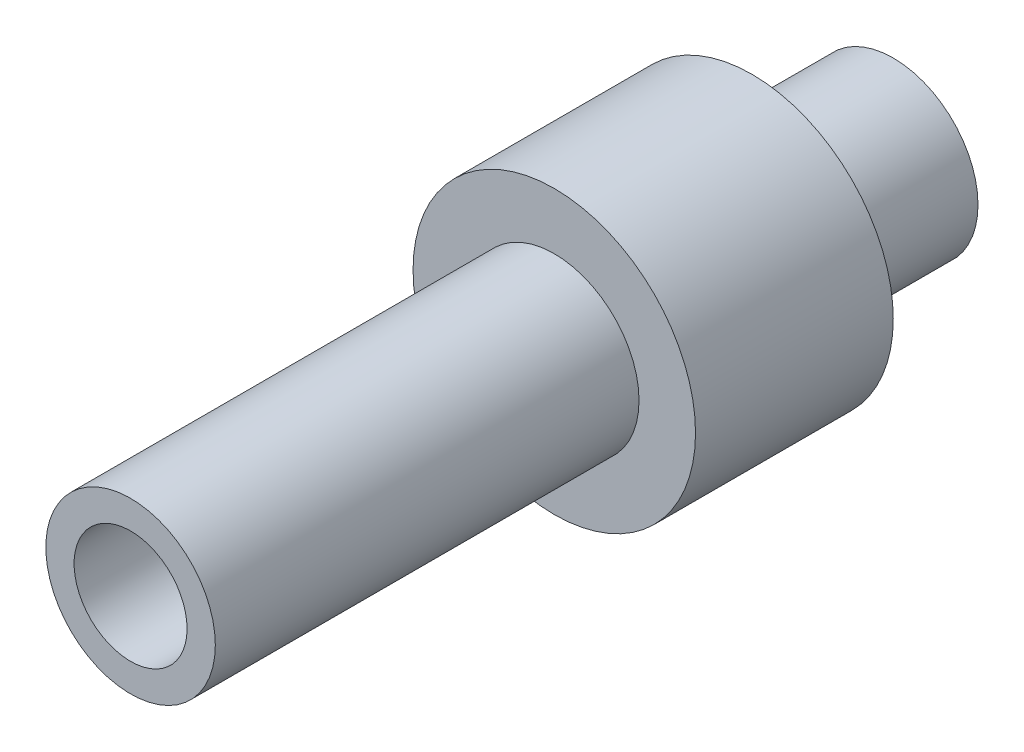
SolidWorks part; units mm, degrees
ref_plane "정면" through (0, 0, 0) normal (0, 0, 1) x (1, 0, 0)
ref_plane "윗면" through (0, 0, 0) normal (0, 1, 0) x (1, 0, 0)
ref_plane "우측면" through (0, 0, 0) normal (1, 0, 0) x (0, 0, -1)
sketch "스케치1" plane through (0, 0, 0) normal (0, 0, 1) x (1, 0, 0)
  circle A0 centre (0, 0) radius 5
extrude "돌출1" add sketch "스케치1" along normal blind 7
sketch "스케치2" plane through (0, 0, 7) normal (0, 0, 1) x (1, 0, 0)
  circle A0 centre (0, 0) radius 3
extrude "돌출2" add sketch "스케치2" along normal blind 15
sketch "스케치3" plane through (0, 0, 0) normal (0, 0, -1) x (-1, 0, 0)
  circle A0 centre (0, 0) radius 3
extrude "돌출3" add sketch "스케치3" along normal blind 5
sketch "스케치4" plane through (0, 0, 22) normal (0, 0, 1) x (1, 0, 0)
  circle A0 centre (0, 0) radius 2
extrude "컷-돌출1" cut sketch "스케치4" against normal blind 27
